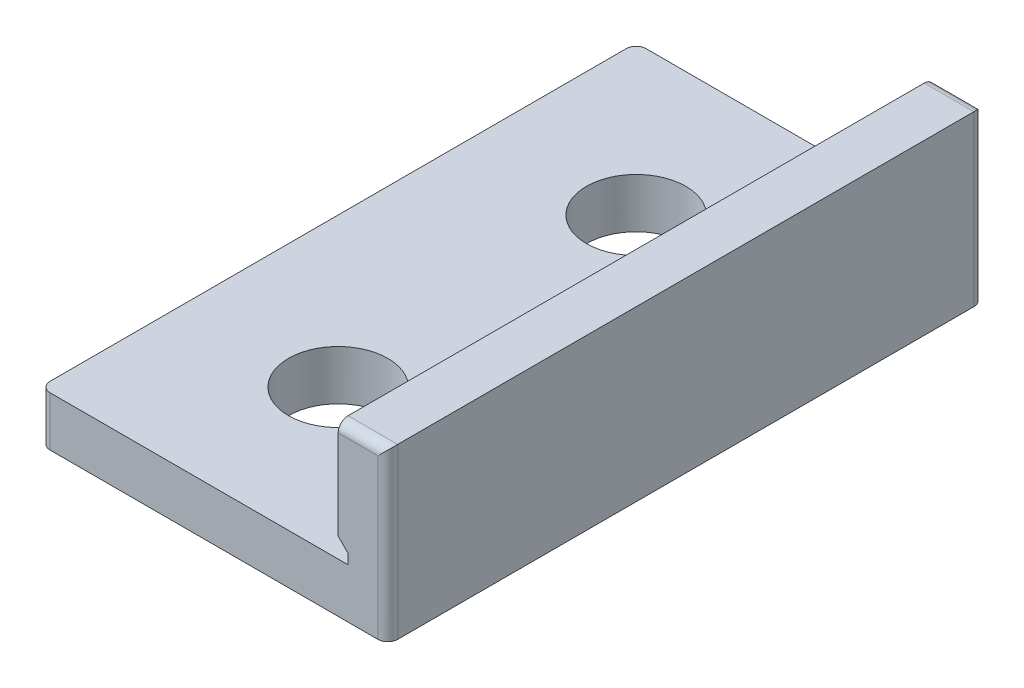
SolidWorks part; units mm, degrees
material "ABS"
ref_plane "Front Plane" through (0, 0, 0) normal (0, 0, 1) x (1, 0, 0)
ref_plane "Top Plane" through (0, 0, 0) normal (0, 1, 0) x (1, 0, 0)
ref_plane "Right Plane" through (0, 0, 0) normal (1, 0, 0) x (0, 0, -1)
sketch "Sketch1" plane through (0, 0, 0) normal (0, 0, 1) x (1, 0, 0)
  line L0 (0, 0) -> (30, 0)
  line L5 (30, 0) -> (30, 12)
  dimension "D1" = 12
  dimension "D2" = 30
extrude "Extrude-Thin1" add sketch "Sketch1" along normal mid plane 60 thin
hole_wizard "M8 Clearance Hole1" positions "Sketch2" profile "Sketch4" hole size "M8" standard "DIN" end condition through all
sketch "Sketch2" plane through (0, -5, 0) normal (0, -1, 0) x (-1, 0, 0)
  line L0 (0, 0) -> (-35, 0) construction
  line L1 (0, -30) -> (0, 30) construction
  line L2 (-35, -30) -> (-35, 30) construction
  line L4 (-15, 0) -> (-15, 15) construction
  point P0 (-15, 15)
  point P2 (-15, -15)
  point P15 (0, 0)
  dimension "D1" = 30
  dimension "D2" = 15
sketch "Sketch4" plane through (15, -5, -15) normal (1, 0, 0) x (0, 0, -1)
  line L0 (0, 0) -> (0, 17)
  line L1 (0, 17) -> (5, 17)
  line L2 (5, 17) -> (5, 0)
  line L5 (5, 0) -> (0, 0)
  line L11 (0, -6.35) -> (0, 107.95) construction
  dimension "Thru Hole Dia." = 10
  dimension "Thru Hole Depth" = 17
sketch "Sketch5" plane through (0, 0, -30) normal (0, 0, -1) x (-1, 0, 0)
  line L0 (-30, 0) -> (-31, 0)
  line L1 (-31, 0) -> (-31, 1)
  line L2 (-31, 1) -> (-30, 2)
  line L3 (-30, 0) -> (-30, 12) construction
  line L4 (-30, 0) -> (-30, 2)
  dimension "D1" = 45
  dimension "D2" = 1
  dimension "D3" = 1
extrude "Cut-Extrude1" cut sketch "Sketch5" against normal up to next
fillet "Fillet1" radius 1 6 edges at (35, 3.5, 30) (35, 3.5, -30) (32.5, 12, 30) (32.5, 12, -30) (0, -2.5, 30) (0, -2.5, -30)
